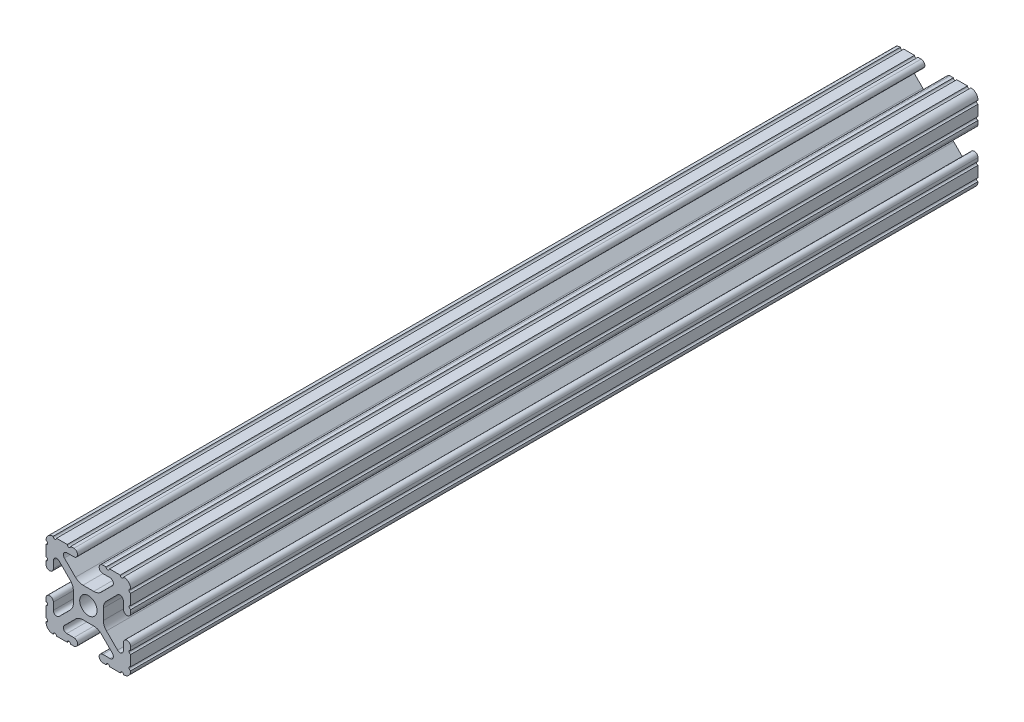
SolidWorks part; units mm, degrees
ref_plane "Front Plane" through (0, 0, 0) normal (0, 0, 1) x (1, 0, 0)
ref_plane "Top Plane" through (0, 0, 0) normal (0, 1, 0) x (1, 0, 0)
ref_plane "Right Plane" through (0, 0, 0) normal (1, 0, 0) x (0, 0, -1)
ref_plane "Plane1" through (0, 0, -101.6) normal (0, 0, -1) x (-1, 0, 0)
sketch "Sketch1" plane through (0, 0, -101.6) normal (0, 0, -1) x (-1, 0, 0)
  line L0 (12.7, -9.5504) -> (12.7, -6.3331)
  line L1 (12.7, -5.3171) -> (12.7, -4.3434)
  line L2 (10.4902, -4.3434) -> (10.4902, -6.4748)
  line L3 (8.7558, -7.1932) -> (5.4257, -3.8632)
  line L4 (4.4958, -1.6181) -> (4.4958, 1.6181)
  line L5 (5.4257, 3.8632) -> (8.7558, 7.1932)
  line L6 (10.4902, 6.4748) -> (10.4902, 4.3434)
  line L7 (12.7, 4.3434) -> (12.7, 5.3171)
  line L8 (12.7, 6.3331) -> (12.7, 9.5504)
  line L9 (9.5504, 12.7) -> (6.3331, 12.7)
  line L10 (5.3171, 12.7) -> (4.3434, 12.7)
  line L11 (4.3434, 10.4902) -> (6.4748, 10.4902)
  line L12 (7.1932, 8.7558) -> (3.8632, 5.4257)
  line L13 (1.6181, 4.4958) -> (-1.6181, 4.4958)
  line L14 (-3.8632, 5.4257) -> (-7.1932, 8.7558)
  line L15 (-6.4748, 10.4902) -> (-4.3434, 10.4902)
  line L16 (-4.3434, 12.7) -> (-5.3171, 12.7)
  line L17 (-6.3331, 12.7) -> (-9.5504, 12.7)
  line L18 (-12.7, 9.5504) -> (-12.7, 6.3331)
  line L19 (-12.7, 5.3171) -> (-12.7, 4.3434)
  line L20 (-10.4902, 4.3434) -> (-10.4902, 6.4748)
  line L21 (-8.7558, 7.1932) -> (-5.4257, 3.8632)
  line L22 (-4.4958, 1.6181) -> (-4.4958, -1.6181)
  line L23 (-5.4257, -3.8632) -> (-8.7558, -7.1932)
  line L24 (-10.4902, -6.4748) -> (-10.4902, -4.3434)
  line L25 (-12.7, -4.3434) -> (-12.7, -5.3171)
  line L26 (-12.7, -6.3331) -> (-12.7, -9.5504)
  line L27 (-9.5504, -12.7) -> (-6.3331, -12.7)
  line L28 (-5.3171, -12.7) -> (-4.3434, -12.7)
  line L29 (-4.3434, -10.4902) -> (-6.4748, -10.4902)
  line L30 (-7.1932, -8.7558) -> (-3.8632, -5.4257)
  line L31 (-1.6181, -4.4958) -> (1.6181, -4.4958)
  line L32 (3.8632, -5.4257) -> (7.1932, -8.7558)
  line L33 (6.4748, -10.4902) -> (4.3434, -10.4902)
  line L34 (4.3434, -12.7) -> (5.3171, -12.7)
  line L35 (6.3331, -12.7) -> (9.5504, -12.7)
  arc A0 (12.6998, -10.5664) -> (12.7, -9.5504) centre (12.7, -10.0584) cw
  arc A1 (12.7, -6.3331) -> (12.7, -5.3171) centre (12.7, -5.8251) cw
  arc A2 (12.7, -4.3434) -> (10.4902, -4.3434) centre (11.5951, -4.3434) ccw
  arc A3 (10.4902, -6.4748) -> (8.7558, -7.1932) centre (9.4742, -6.4748) cw
  arc A4 (5.4257, -3.8632) -> (4.4958, -1.6181) centre (7.6708, -1.6181) cw
  arc A5 (4.4958, 1.6181) -> (5.4257, 3.8632) centre (7.6708, 1.6181) cw
  arc A6 (8.7558, 7.1932) -> (10.4902, 6.4748) centre (9.4742, 6.4748) cw
  arc A7 (10.4902, 4.3434) -> (12.7, 4.3434) centre (11.5951, 4.3434) ccw
  arc A8 (12.7, 5.3171) -> (12.7, 6.3331) centre (12.7, 5.8251) cw
  arc A9 (12.7, 9.5504) -> (12.6998, 10.5664) centre (12.7, 10.0584) cw
  arc A10 (12.6998, 10.5664) -> (10.5664, 12.6998) centre (10.5918, 10.5918) ccw
  arc A11 (10.5664, 12.6998) -> (9.5504, 12.7) centre (10.0584, 12.7) cw
  arc A12 (6.3331, 12.7) -> (5.3171, 12.7) centre (5.8251, 12.7) cw
  arc A13 (4.3434, 12.7) -> (4.3434, 10.4902) centre (4.3434, 11.5951) ccw
  arc A14 (6.4748, 10.4902) -> (7.1932, 8.7558) centre (6.4748, 9.4742) cw
  arc A15 (3.8632, 5.4257) -> (1.6181, 4.4958) centre (1.6181, 7.6708) cw
  arc A16 (-1.6181, 4.4958) -> (-3.8632, 5.4257) centre (-1.6181, 7.6708) cw
  arc A17 (-7.1932, 8.7558) -> (-6.4748, 10.4902) centre (-6.4748, 9.4742) cw
  arc A18 (-4.3434, 10.4902) -> (-4.3434, 12.7) centre (-4.3434, 11.5951) ccw
  arc A19 (-5.3171, 12.7) -> (-6.3331, 12.7) centre (-5.8251, 12.7) cw
  arc A20 (-9.5504, 12.7) -> (-10.5664, 12.6998) centre (-10.0584, 12.7) cw
  arc A21 (-10.5664, 12.6998) -> (-12.6998, 10.5664) centre (-10.5918, 10.5918) ccw
  arc A22 (-12.6998, 10.5664) -> (-12.7, 9.5504) centre (-12.7, 10.0584) cw
  arc A23 (-12.7, 6.3331) -> (-12.7, 5.3171) centre (-12.7, 5.8251) cw
  arc A24 (-12.7, 4.3434) -> (-10.4902, 4.3434) centre (-11.5951, 4.3434) ccw
  arc A25 (-10.4902, 6.4748) -> (-8.7558, 7.1932) centre (-9.4742, 6.4748) cw
  arc A26 (-5.4257, 3.8632) -> (-4.4958, 1.6181) centre (-7.6708, 1.6181) cw
  arc A27 (-4.4958, -1.6181) -> (-5.4257, -3.8632) centre (-7.6708, -1.6181) cw
  arc A28 (-8.7558, -7.1932) -> (-10.4902, -6.4748) centre (-9.4742, -6.4748) cw
  arc A29 (-10.4902, -4.3434) -> (-12.7, -4.3434) centre (-11.5951, -4.3434) ccw
  arc A30 (-12.7, -5.3171) -> (-12.7, -6.3331) centre (-12.7, -5.8251) cw
  arc A31 (-12.7, -9.5504) -> (-12.6998, -10.5664) centre (-12.7, -10.0584) cw
  arc A32 (-12.6998, -10.5664) -> (-10.5664, -12.6998) centre (-10.5918, -10.5918) ccw
  arc A33 (-10.5664, -12.6998) -> (-9.5504, -12.7) centre (-10.0584, -12.7) cw
  arc A34 (-6.3331, -12.7) -> (-5.3171, -12.7) centre (-5.8251, -12.7) cw
  arc A35 (-4.3434, -12.7) -> (-4.3434, -10.4902) centre (-4.3434, -11.5951) ccw
  arc A36 (-6.4748, -10.4902) -> (-7.1932, -8.7558) centre (-6.4748, -9.4742) cw
  arc A37 (-3.8632, -5.4257) -> (-1.6181, -4.4958) centre (-1.6181, -7.6708) cw
  arc A38 (1.6181, -4.4958) -> (3.8632, -5.4257) centre (1.6181, -7.6708) cw
  arc A39 (7.1932, -8.7558) -> (6.4748, -10.4902) centre (6.4748, -9.4742) cw
  arc A40 (4.3434, -10.4902) -> (4.3434, -12.7) centre (4.3434, -11.5951) ccw
  arc A41 (5.3171, -12.7) -> (6.3331, -12.7) centre (5.8251, -12.7) cw
  arc A42 (9.5504, -12.7) -> (10.5664, -12.6998) centre (10.0584, -12.7) cw
  arc A43 (10.5664, -12.6998) -> (12.6998, -10.5664) centre (10.5918, -10.5918) ccw
  circle A44 centre (0, 0) radius 2.6035
extrude "Boss-Extrude1" add sketch "Sketch1" against normal blind 254
